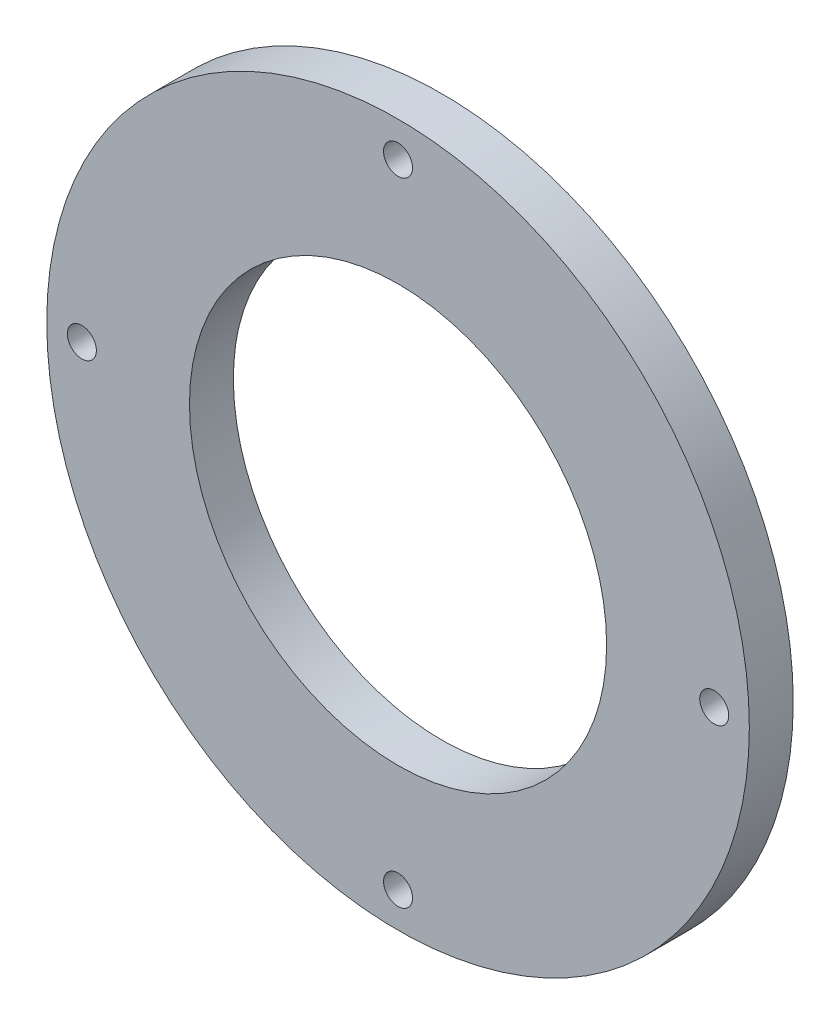
SolidWorks part; units mm, degrees
ref_plane "Спереди" through (0, 0, 0) normal (0, 0, 1) x (1, 0, 0)
ref_plane "Сверху" through (0, 0, 0) normal (0, 1, 0) x (1, 0, 0)
ref_plane "Справа" through (0, 0, 0) normal (1, 0, 0) x (0, 0, -1)
other "Configuration Table"
sketch "Eskiz_kontur" plane through (0, 0, 0) normal (0, 0, 1) x (1, 0, 0)
  circle A0 centre (0, 0) radius 40
extrude "Plastina" add sketch "Eskiz_kontur" along normal blind 5
sketch "Eskiz_otverstiya" plane through (0, 0, 0) normal (0, 0, 1) x (1, 0, 0)
  circle A0 centre (0, -36) radius 1.65
  circle A1 centre (0, 0) radius 23.75
  circle A2 centre (-36, 0) radius 1.65
  circle A3 centre (36, 0) radius 1.65
  circle A4 centre (0, 36) radius 1.65
  dimension "d1" = 3.3
  dimension "d2" = 47.5
  dimension "d3" = 3.3
  dimension "d4" = 3.3
  dimension "d5" = 3.3
extrude "Otverstiya" cut sketch "Eskiz_otverstiya" against normal through all and the other way through all
equation "\"T3\" = 3"
equation "\"T5\" = 5"
equation "\"D_M3\" = 3.3"
equation "\"D_M2\" = 2.2"
equation "\"D_M3_TAP\" = 2.5"
equation "\"D_M4\" = 4.5"
equation "\"L1\" = 100"
equation "\"L2\" = 100"
equation "\"D1@Plastina\" = \"T5\""
equation "\"d1@Eskiz_otverstiya\" = \"D_M3\""
equation "\"d3@Eskiz_otverstiya\" = \"D_M3\""
equation "\"d4@Eskiz_otverstiya\" = \"D_M3\""
equation "\"d5@Eskiz_otverstiya\" = \"D_M3\""
